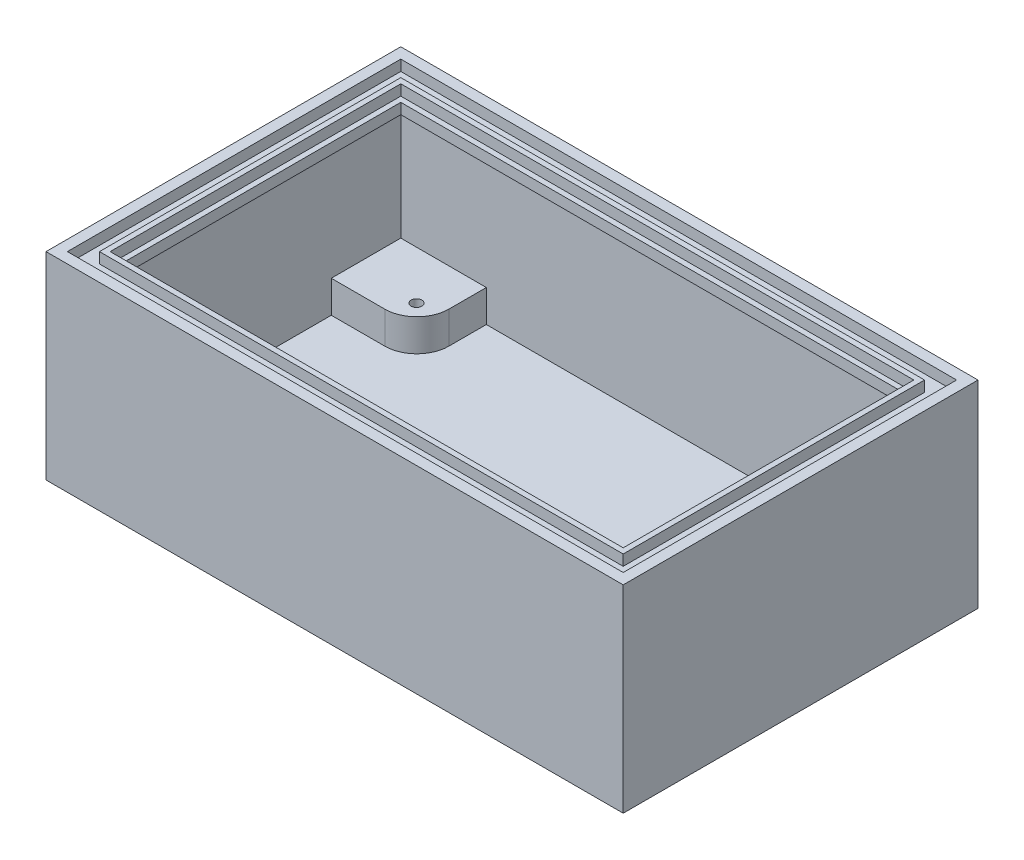
SolidWorks part; units mm, degrees
ref_plane "Front Plane" through (0, 0, 0) normal (0, 0, 1) x (1, 0, 0)
ref_plane "Top Plane" through (0, 0, 0) normal (0, 1, 0) x (1, 0, 0)
ref_plane "Right Plane" through (0, 0, 0) normal (1, 0, 0) x (0, 0, -1)
sketch "Sketch1" plane through (0, 0, 0) normal (0, 1, 0) x (1, 0, 0)
  line L0 (-45.9867, 25.1841) -> (-51.9867, 25.1841) construction
  line L1 (-45.9867, 25.1841) -> (45.9867, 25.1841) construction
  line L2 (-45.9867, 25.1841) -> (-45.9867, -25.1841) construction
  line L3 (-45.9867, -25.1841) -> (45.9867, -25.1841) construction
  line L4 (45.9867, 25.1841) -> (45.9867, -25.1841) construction
  line L5 (-45.9867, 25.1841) -> (45.9867, -25.1841) construction
  line L6 (-45.9867, -25.1841) -> (45.9867, 25.1841) construction
  line L7 (-51.9867, 31.1841) -> (51.9867, 31.1841)
  line L8 (-51.9867, 31.1841) -> (-51.9867, -31.1841)
  line L9 (-51.9867, -31.1841) -> (51.9867, -31.1841)
  line L10 (51.9867, 31.1841) -> (51.9867, -31.1841)
  line L11 (-51.9867, 31.1841) -> (51.9867, -31.1841) construction
  line L12 (-51.9867, -31.1841) -> (51.9867, 31.1841) construction
  line L13 (-53.9867, -33.1841) -> (53.9867, -33.1841)
  line L14 (-53.9867, -33.1841) -> (-53.9867, 33.1841)
  line L15 (-53.9867, 33.1841) -> (53.9867, 33.1841)
  line L16 (53.9867, -33.1841) -> (53.9867, 33.1841)
  line L17 (-53.9867, -33.1841) -> (53.9867, 33.1841) construction
  line L18 (-53.9867, 33.1841) -> (53.9867, -33.1841) construction
  line L19 (-45.9867, 25.1841) -> (-45.9867, 31.1841) construction
  line L20 (-51.9867, 31.1841) -> (-51.9867, 33.1841) construction
  line L22 (-53.9867, 31.1841) -> (-51.9867, 31.1841) construction
  point P0 (0, 0)
  point P6 (0, 0)
  point P11 (0, 0)
  point P19 (0, 0)
  dimension "D1" = 91.9734
  dimension "D2" = 50.3682
  dimension "D3" = 6
  dimension "D4" = 2
extrude "Boss-Extrude1" add sketch "Sketch1" along normal blind 35
sketch "Sketch7" plane through (0, 0, 0) normal (0, 1, 0) x (1, 0, 0)
  line L0 (51.9867, 31.1841) -> (51.9867, -31.1841) construction
  line L1 (-42.9867, -25.1841) -> (48.9867, -25.1841) construction
  line L2 (-42.9867, -25.1841) -> (-42.9867, 25.1841) construction
  line L3 (-42.9867, 25.1841) -> (48.9867, 25.1841) construction
  line L4 (48.9867, -25.1841) -> (48.9867, 25.1841) construction
  line L5 (-42.9867, -25.1841) -> (48.9867, 25.1841) construction
  line L6 (-42.9867, 25.1841) -> (48.9867, -25.1841) construction
  point P0 (3, 0)
  point P5 (0, 0)
  point P7 (2.3242, 0)
  point P8 (1.6952, 0)
  dimension "D1" = 50.3682
  dimension "D2" = 91.9734
  dimension "D3" = 3
  dimension "D4" = 3
sketch "Sketch2" plane through (0, 0, 0) normal (0, -1, 0) x (1, 0, 0)
  line L1 (-53.9867, 33.1841) -> (53.9867, 33.1841)
  line L2 (-53.9867, 33.1841) -> (-53.9867, -33.1841)
  line L3 (-53.9867, -33.1841) -> (53.9867, -33.1841)
  line L4 (53.9867, 33.1841) -> (53.9867, -33.1841)
  line L5 (-53.9867, 33.1841) -> (53.9867, -33.1841) construction
  line L6 (-53.9867, -33.1841) -> (53.9867, 33.1841) construction
  point P0 (0, 0)
extrude "Boss-Extrude2" add sketch "Sketch2" along normal blind 2
sketch "Sketch4" plane through (0, 0, 0) normal (0, 1, 0) x (1, 0, 0)
  line L0 (3, 10.8917) -> (3, 0) construction
  line L5 (-39.9883, -22.1209) -> (45.9882, -22.1209) construction
  line L7 (-39.9883, -22.1209) -> (-39.9883, 22.1209) construction
  line L8 (-39.9883, 22.1209) -> (45.9882, 22.1209) construction
  line L9 (45.9882, -22.1209) -> (45.9882, 22.1209) construction
  line L10 (-39.9883, -22.1209) -> (45.9882, 22.1209) construction
  line L11 (-39.9883, 22.1209) -> (45.9882, -22.1209) construction
  line L12 (3, 0) -> (16.4905, 0) construction
  circle A4 centre (-39.9883, 22.1209) radius 1
  circle A5 centre (45.9882, 22.1209) radius 1
  circle A6 centre (45.9882, -22.1209) radius 1
  circle A7 centre (-39.9883, -22.1209) radius 1
  point P0 (3, 0)
  dimension "D3" = 2
  dimension "D1" = 85.9765
  dimension "D2" = 44.2417
sketch "Sketch3" plane through (0, 0, 0) normal (0, 1, 0) x (1, 0, 0)
  line L0 (-51.9867, 18.1841) -> (-51.9867, 31.1841)
  line L1 (-51.9867, 31.1841) -> (-51.9867, -31.1841) construction
  line L2 (-51.9867, 31.1841) -> (-35.9867, 31.1841)
  line L3 (51.9867, 31.1841) -> (-51.9867, 31.1841) construction
  line L4 (0, 7.1792) -> (0, 0) construction
  line L5 (0, 0) -> (7.7262, 0) construction
  line L12 (-35.9867, 31.1841) -> (-35.9867, 24.1841)
  line L13 (-51.9867, 18.1841) -> (-41.9867, 18.1841)
  line L14 (-41.9867, 24.1841) -> (-42.9867, 25.1841) construction
  line L15 (-41.9867, 18.1841) -> (-35.9867, 18.1841) construction
  line L16 (-35.9867, 18.1841) -> (-35.9867, 24.1841) construction
  line L17 (51.9867, 18.1841) -> (47.9867, 18.1841)
  line L18 (51.9867, 18.1841) -> (51.9867, 31.1841)
  line L19 (51.9867, 31.1841) -> (41.9867, 31.1841)
  line L20 (41.9867, 31.1841) -> (41.9867, 24.1841)
  line L21 (-35.9867, -18.1841) -> (-35.9867, -24.1841) construction
  line L22 (-41.9867, -18.1841) -> (-35.9867, -18.1841) construction
  line L23 (-51.9867, -31.1841) -> (-35.9867, -18.1841) construction
  line L24 (41.9867, -31.1841) -> (41.9867, -24.1841)
  line L25 (51.9867, -31.1841) -> (41.9867, -31.1841)
  line L26 (51.9867, -18.1841) -> (51.9867, -31.1841)
  line L27 (51.9867, -18.1841) -> (47.9867, -18.1841)
  line L28 (-51.9867, -18.1841) -> (-41.9867, -18.1841)
  line L29 (-35.9867, -31.1841) -> (-35.9867, -24.1841)
  line L30 (-51.9867, -31.1841) -> (-35.9867, -31.1841)
  line L31 (-51.9867, -18.1841) -> (-51.9867, -31.1841)
  line L32 (47.9867, 24.1841) -> (48.9867, 25.1841) construction
  arc A4 (-41.9867, 18.1841) -> (-35.9867, 24.1841) centre (-41.9867, 24.1841) ccw
  arc A5 (47.9867, 18.1841) -> (41.9867, 24.1841) centre (47.9867, 24.1841) cw
  arc A6 (47.9867, -18.1841) -> (41.9867, -24.1841) centre (47.9867, -24.1841) ccw
  arc A7 (-41.9867, -18.1841) -> (-35.9867, -24.1841) centre (-41.9867, -24.1841) cw
  dimension "D3" = 6
  dimension "D5" = 6
  dimension "D1" = 13
  dimension "D2" = 7
  dimension "D4" = 45
  dimension "D6" = 45
extrude "Boss-Extrude3" add sketch "Sketch3" along normal blind 6
extrude "Cut-Extrude1" cut sketch "Sketch4" along normal up to next from offset 3
ref_plane "Plane1" through (0, 31, 0) normal (0, 1, 0) x (1, 0, 0)
sketch "Sketch5" plane through (0, 31, 0) normal (0, 1, 0) x (1, 0, 0)
  line L0 (-51.9867, 26.1841) -> (-46.9867, 26.1841) construction
  line L1 (-51.9867, 31.1841) -> (51.9867, 31.1841)
  line L2 (-51.9867, 31.1841) -> (-51.9867, -31.1841)
  line L3 (-51.9867, -31.1841) -> (51.9867, -31.1841)
  line L4 (51.9867, 31.1841) -> (51.9867, -31.1841)
  line L5 (-51.9867, 31.1841) -> (51.9867, -31.1841) construction
  line L6 (-51.9867, -31.1841) -> (51.9867, 31.1841) construction
  line L7 (-46.9867, 26.1841) -> (46.9867, 26.1841)
  line L8 (-46.9867, 26.1841) -> (-46.9867, -26.1841)
  line L9 (-46.9867, -26.1841) -> (46.9867, -26.1841)
  line L10 (46.9867, 26.1841) -> (46.9867, -26.1841)
  line L11 (-46.9867, 26.1841) -> (46.9867, -26.1841) construction
  line L12 (-46.9867, -26.1841) -> (46.9867, 26.1841) construction
  line L13 (-46.9867, 26.1841) -> (-46.9867, 31.1841) construction
  point P0 (0, 0)
  point P7 (0, 0)
  dimension "D1" = 5
extrude "Boss-Extrude4" add sketch "Sketch5" along normal offset from surface (2 mm away) 2 up to face at (0, 35, 0)
sketch "Sketch6" plane through (0, 33, 0) normal (0, 1, 0) x (1, 0, 0)
  line L0 (-48.9867, 27.1841) -> (-47.9867, 27.1841) construction
  line L1 (47.9867, -27.1841) -> (-47.9867, -27.1841)
  line L2 (47.9867, -27.1841) -> (47.9867, 27.1841)
  line L3 (47.9867, 27.1841) -> (-47.9867, 27.1841)
  line L4 (-47.9867, -27.1841) -> (-47.9867, 27.1841)
  line L5 (47.9867, -27.1841) -> (-47.9867, 27.1841) construction
  line L6 (47.9867, 27.1841) -> (-47.9867, -27.1841) construction
  line L7 (48.9867, -28.1841) -> (-48.9867, -28.1841)
  line L8 (48.9867, -28.1841) -> (48.9867, 28.1841)
  line L9 (48.9867, 28.1841) -> (-48.9867, 28.1841)
  line L10 (-48.9867, -28.1841) -> (-48.9867, 28.1841)
  line L11 (48.9867, -28.1841) -> (-48.9867, 28.1841) construction
  line L12 (48.9867, 28.1841) -> (-48.9867, -28.1841) construction
  line L13 (-47.9867, 28.1841) -> (-47.9867, 27.1841) construction
  line L14 (-46.9867, 26.1841) -> (-46.9867, 27.1841) construction
  line L16 (-47.9867, 26.1841) -> (-46.9867, 26.1841) construction
  point P0 (0, 0)
  point P7 (0, 0)
  dimension "D1" = 1
  dimension "D2" = 1
extrude "Boss-Extrude5" add sketch "Sketch6" along normal up to surface (2 mm away) up to face at (0, 35, 0)
sketch "Sketch8" plane through (0, 0, 0) normal (0, 1, 0) x (1, 0, 0)
  line L0 (0, 0) -> (0, 10.9672) construction
  line L1 (-45, -3.5) -> (45, -3.5) construction
  line L2 (-45, -3.5) -> (-45, -16.5) construction
  line L3 (-45, -16.5) -> (45, -16.5) construction
  line L4 (45, -3.5) -> (45, -16.5) construction
  line L5 (-45, -3.5) -> (45, -16.5) construction
  line L6 (-45, -16.5) -> (45, -3.5) construction
  line L7 (-46.5, -7.5) -> (-45.5, -7.5)
  line L8 (-46.5, -7.5) -> (-46.5, -12.5)
  line L9 (-46.5, -12.5) -> (-45.5, -12.5)
  line L10 (-45.5, -7.5) -> (-45.5, -12.5)
  line L11 (-46.5, -7.5) -> (-45.5, -12.5) construction
  line L12 (-46.5, -12.5) -> (-45.5, -7.5) construction
  line L17 (46.5, -12.5) -> (45.5, -7.5) construction
  line L18 (46.5, -7.5) -> (45.5, -12.5) construction
  line L19 (45.5, -7.5) -> (45.5, -12.5)
  line L20 (46.5, -12.5) -> (45.5, -12.5)
  line L21 (46.5, -7.5) -> (46.5, -12.5)
  line L22 (46.5, -7.5) -> (45.5, -7.5)
  line L23 (32.5, -18) -> (27.5, -17) construction
  line L24 (-32.5, -17) -> (-27.5, -17)
  line L25 (-32.5, -17) -> (-32.5, -18)
  line L26 (-32.5, -18) -> (-27.5, -18)
  line L27 (-27.5, -17) -> (-27.5, -18)
  line L28 (-32.5, -17) -> (-27.5, -18) construction
  line L29 (-32.5, -18) -> (-27.5, -17) construction
  line L30 (32.5, -17) -> (27.5, -18) construction
  line L31 (27.5, -17) -> (27.5, -18)
  line L32 (32.5, -18) -> (27.5, -18)
  line L33 (32.5, -17) -> (32.5, -18)
  line L34 (32.5, -17) -> (27.5, -17)
  point P0 (0, -10)
  point P5 (-46, -10)
  point P17 (46, -10)
  point P18 (-30, -17.5)
  point P27 (30, -17.5)
  dimension "D1" = 90
  dimension "D2" = 13
  dimension "D3" = 1
  dimension "D4" = 5
  dimension "D5" = 0.5
  dimension "D6" = 30
  dimension "D7" = 0.5
  dimension "D8" = 10
extrude "Boss-Extrude6" add sketch "Sketch8" along normal blind 1.5
sketch "Sketch9" plane through (0, 0, 0) normal (0, 1, 0) x (1, 0, 0)
  line L5 (-45, -3.5) -> (45, -3.5) construction
  circle A0 centre (0, -0.5) radius 2.5
  point P2 (0, 0)
  point P3 (0, -0.9283)
  dimension "D1" = 5
  dimension "D2" = 3
extrude "Boss-Extrude7" add sketch "Sketch9" along normal blind 1.8
sketch "Sketch12" plane through (0, 1.8, 0) normal (0, 1, 0) x (1, 0, 0)
  circle A0 centre (0, -0.5) radius 0.75
  circle A1 centre (0, -0.5) radius 2.5 construction
  dimension "D1" = 1.5
extrude "Boss-Extrude8" add sketch "Sketch12" along normal blind 1.5
sketch "Sketch13" plane through (0, 1.8, 0) normal (0, 1, 0) x (1, 0, 0)
  line L0 (-2.4206, -1.125) -> (-1.4524, -4.875)
  line L1 (1.4524, -4.875) -> (2.4206, -1.125)
  arc A0 (2.4206, -1.125) -> (-2.4206, -1.125) centre (0, -0.5) ccw
  circle A1 centre (0, -0.5) radius 2.5 construction
  circle A2 centre (0, -0.5) radius 1.25
  circle A3 centre (0, -0.5) radius 0.75 construction
  arc A4 (-1.4524, -4.875) -> (1.4524, -4.875) centre (0, -4.5) ccw
  arc A5 (0, -3) -> (-1.4524, -4.875) centre (0, -4.5) ccw construction
  arc A6 (1.4524, -4.875) -> (0, -3) centre (0, -4.5) ccw construction
  arc A7 (0, -3) -> (2.4206, -1.125) centre (0, -0.5) ccw construction
  arc A8 (-2.4206, -1.125) -> (0, -3) centre (0, -0.5) ccw construction
  dimension "D1" = 0.5
  dimension "D2" = 3
  dimension "D3" = 4
extrude "Boss-Extrude9" add sketch "Sketch13" along normal blind 1 from offset 0.25 separate body
sketch "Sketch14" plane through (0, 3.3, 0) normal (0, 1, 0) x (1, 0, 0)
  circle A0 centre (0, -0.5) radius 2.5
  circle A1 centre (0, -0.5) radius 2.5 construction
extrude "Boss-Extrude10" add sketch "Sketch14" along normal blind 1
